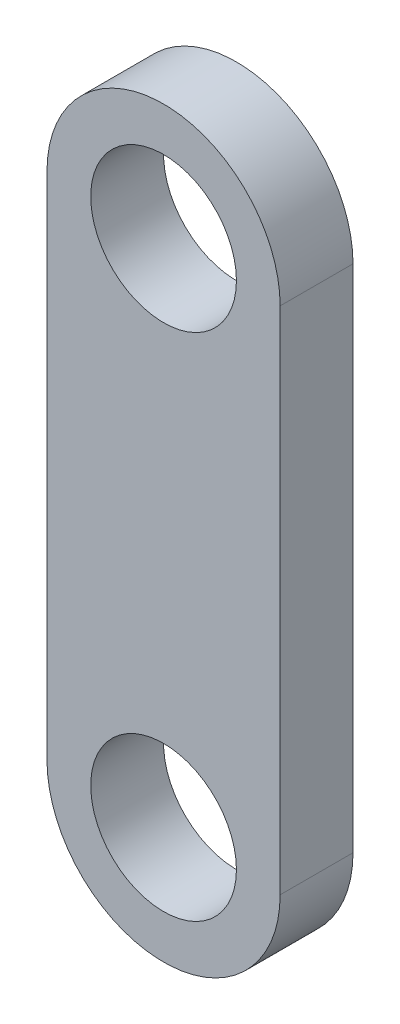
SolidWorks part; units mm, degrees
ref_plane "前基準面" through (0, 0, 0) normal (0, 0, 1) x (1, 0, 0)
ref_plane "上基準面" through (0, 0, 0) normal (0, 1, 0) x (1, 0, 0)
ref_plane "右基準面" through (0, 0, 0) normal (1, 0, 0) x (0, 0, -1)
sketch "草圖1" plane through (0, 0, 0) normal (0, 0, 1) x (1, 0, 0)
  line L0 (0, -1.75) -> (0, 1.75) construction
  line L1 (-0.8, -1.75) -> (-0.8, 1.75)
  line L2 (0.8, -1.75) -> (0.8, 1.75)
  arc A0 (-0.8, -1.75) -> (0.8, -1.75) centre (0, -1.75) ccw
  arc A1 (0.8, 1.75) -> (-0.8, 1.75) centre (0, 1.75) ccw
  circle A2 centre (0, 1.75) radius 0.5
  circle A3 centre (0, -1.75) radius 0.5
  point P2 (0, 0)
  dimension "D1" = 1
  dimension "D2" = 0.8
  dimension "D4" = 1
  dimension "D3" = 3.5
extrude "填料-伸長1" add sketch "草圖1" along normal blind 0.5
